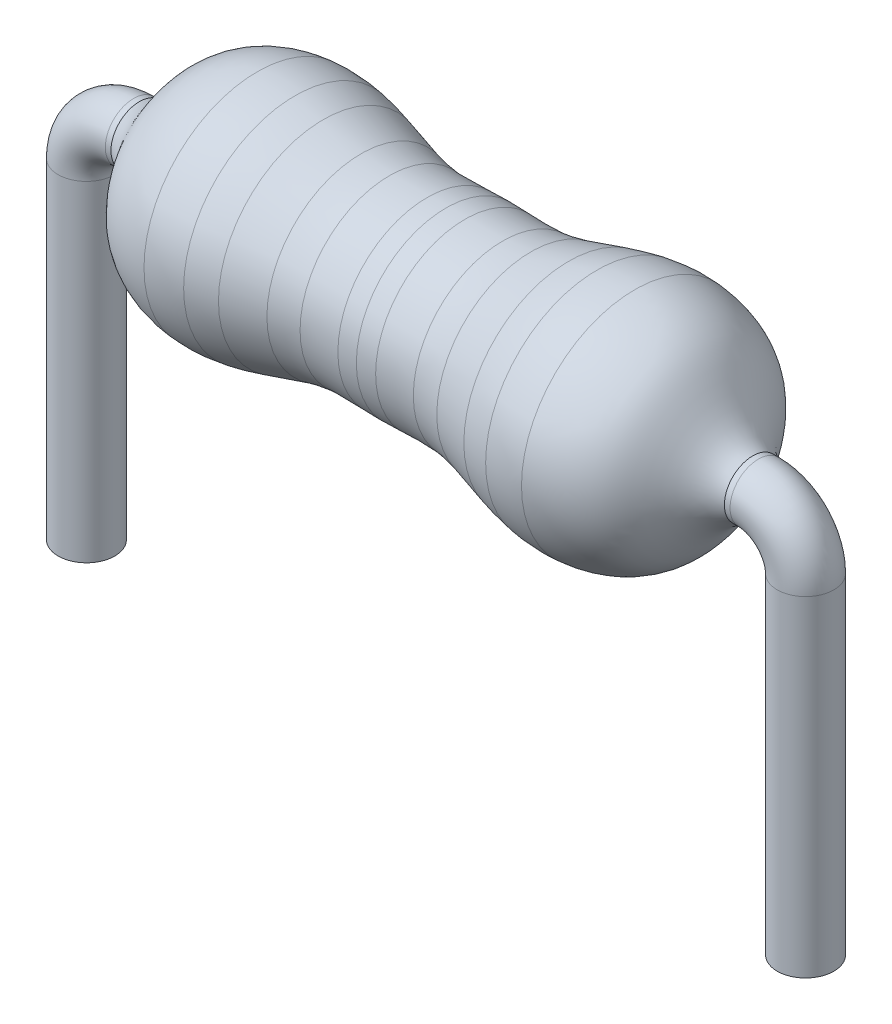
SolidWorks part; units mm, degrees
ref_plane "Front Plane" through (0, 0, 0) normal (0, 0, 1) x (1, 0, 0)
ref_plane "Top Plane" through (0, 0, 0) normal (0, 1, 0) x (1, 0, 0)
ref_plane "Right Plane" through (0, 0, 0) normal (1, 0, 0) x (0, 0, -1)
sketch "Эскиз3" plane through (0, 0, 0) normal (0, 0, 1) x (1, 0, 0)
  line L0 (0, 0) -> (0, 0.95) construction
  line L1 (0, 0) -> (-3.25, 0)
  line L2 (-3.25, 0.3) -> (-3.25, 0)
  line L3 (3.25, 0.3) -> (3.25, 0)
  line L4 (0, 0) -> (3.25, 0)
  spline S7 degree 3 poles (-2, 1.2) (-2.236, 1.1816) (-2.7893, 1.0051) (-2.9711, 0.4301) (-3.25, 0.3) knots 0.780397 0.780397 0.780397 0.780397 0.876745 1 1 1 1
  spline S8 degree 3 poles (-1.6, 1.18) (-1.7314, 1.2017) (-1.8646, 1.2105) (-2, 1.2) knots 0.725131 0.725131 0.725131 0.725131 0.780397 0.780397 0.780397 0.780397
  spline S9 degree 3 poles (-1.3, 1.1111) (-1.3498, 1.125) (-1.4493, 1.1514) (-1.5497, 1.1718) (-1.6, 1.18) knots 0.682659 0.682659 0.682659 0.682659 0.703993 0.725131 0.725131 0.725131 0.725131
  spline S10 degree 3 poles (-0.9, 0.9977) (-1.0336, 1.0307) (-1.1663, 1.0735) (-1.3, 1.1111) knots 0.625412 0.625412 0.625412 0.625412 0.682659 0.682659 0.682659 0.682659
  spline S11 degree 3 poles (-0.6, 0.9462) (-0.6167, 0.9476) (-0.7176, 0.9571) (-0.8172, 0.9772) (-0.9, 0.9977) knots 0.58292 0.58292 0.58292 0.58292 0.589942 0.625412 0.625412 0.625412 0.625412
  spline S12 degree 3 poles (-0.2, 0.9457) (-0.3344, 0.9411) (-0.4682, 0.9358) (-0.6, 0.9462) knots 0.527476 0.527476 0.527476 0.527476 0.58292 0.58292 0.58292 0.58292
  spline S13 degree 3 poles (0, 0.95) (-0.0667, 0.9501) (-0.1334, 0.948) (-0.2, 0.9457) knots 0.500017 0.500017 0.500017 0.500017 0.527476 0.527476 0.527476 0.527476
  spline S14 degree 3 poles (0, 0.95) (0.0667, 0.9501) (0.1334, 0.948) (0.2, 0.9457) knots 0.500017 0.500017 0.500017 0.500017 0.527476 0.527476 0.527476 0.527476
  spline S15 degree 3 poles (0.2, 0.9457) (0.3344, 0.9411) (0.4682, 0.9358) (0.6, 0.9462) knots 0.527476 0.527476 0.527476 0.527476 0.58292 0.58292 0.58292 0.58292
  spline S16 degree 3 poles (0.6, 0.9462) (0.6167, 0.9476) (0.7176, 0.9571) (0.8172, 0.9772) (0.9, 0.9977) knots 0.58292 0.58292 0.58292 0.58292 0.589942 0.625412 0.625412 0.625412 0.625412
  spline S17 degree 3 poles (0.9, 0.9977) (1.0336, 1.0307) (1.1663, 1.0735) (1.3, 1.1111) knots 0.625412 0.625412 0.625412 0.625412 0.682659 0.682659 0.682659 0.682659
  spline S18 degree 3 poles (1.3, 1.1111) (1.3498, 1.125) (1.4493, 1.1514) (1.5497, 1.1718) (1.6, 1.18) knots 0.682659 0.682659 0.682659 0.682659 0.703993 0.725131 0.725131 0.725131 0.725131
  spline S19 degree 3 poles (1.6, 1.18) (1.7314, 1.2017) (1.8646, 1.2105) (2, 1.2) knots 0.725131 0.725131 0.725131 0.725131 0.780397 0.780397 0.780397 0.780397
  spline S20 degree 3 poles (2, 1.2) (2.236, 1.1816) (2.7893, 1.0051) (2.9711, 0.4301) (3.25, 0.3) knots 0.780397 0.780397 0.780397 0.780397 0.876745 1 1 1 1
sketch "Эскиз4" plane through (0, 0, 0) normal (0, 0, 1) x (1, 0, 0)
  line L0 (2.9873, 0) -> (3.31, 0)
  line L1 (3.81, -0.5) -> (3.81, -4)
  arc A0 (3.81, -0.5) -> (3.31, 0) centre (3.31, -0.5) ccw
  dimension "D2" = 0.5
  dimension "D1" = 3.81
  dimension "D3" = 4
ref_plane "Плоскость1" through (0, -4, 0) normal (0, 1, 0) x (1, 0, 0)
sketch "Эскиз5" plane through (0, -4, 0) normal (0, 1, 0) x (1, 0, 0)
  circle A0 centre (3.81, 0) radius 0.3
  dimension "D1" = 0.6
revolve "Повернуть2" add sketch "Эскиз3" angle 360 about L4
sweep "По траектории2" add profiles "Эскиз5" path "Эскиз4"
mirror "Зеркальное отражение1" about plane through (0, 0, 0) normal (1, 0, 0) of "По траектории2"
